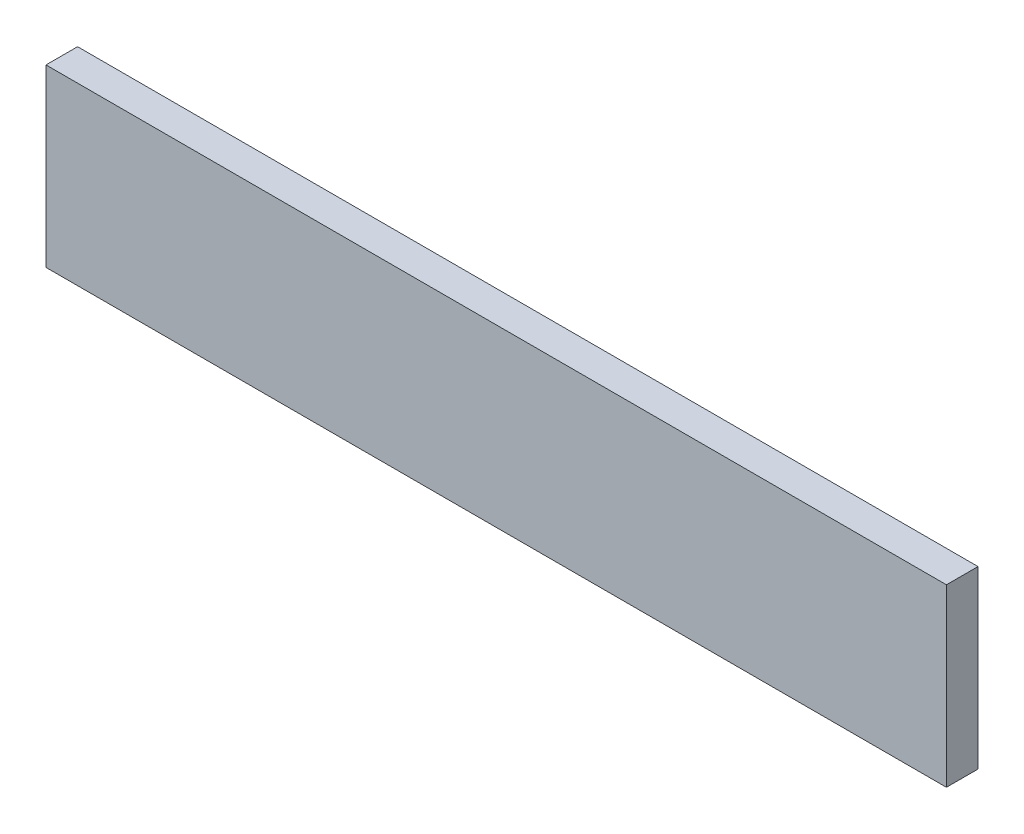
SolidWorks part; units mm, degrees
ref_plane "Front" through (0, 0, 0) normal (0, 0, 1) x (1, 0, 0)
ref_plane "Top" through (0, 0, 0) normal (0, 1, 0) x (1, 0, 0)
ref_plane "Right" through (0, 0, 0) normal (1, 0, 0) x (0, 0, -1)
sketch "Esquisse1" plane through (0, 0, 0) normal (0, 0, 1) x (1, 0, 0)
  line L1 (0, 0) -> (770, 0)
  line L2 (0, 0) -> (0, 150)
  line L3 (0, 150) -> (770, 150)
  line L4 (770, 0) -> (770, 150)
  dimension "D1" = 150
  dimension "D2" = 770
extrude "Boss.-Extru.1" add sketch "Esquisse1" along normal blind 27
